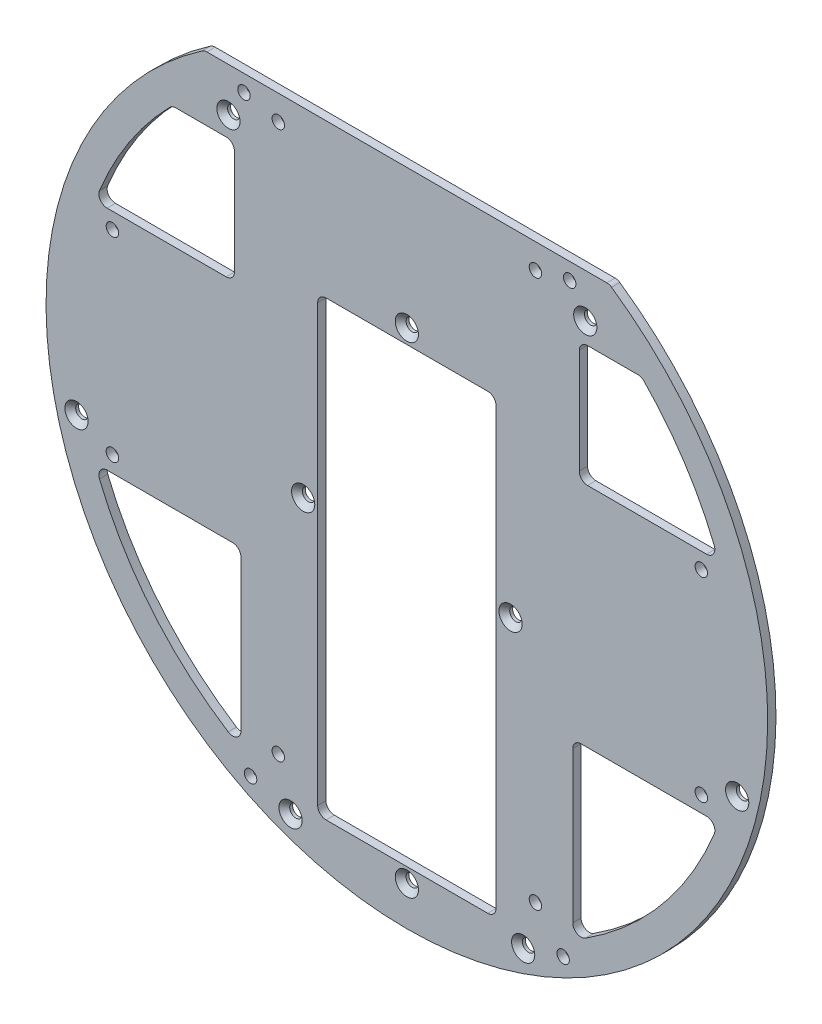
SolidWorks part; units mm, degrees
material "6061 Alloy"
ref_plane "Front Plane" through (0, 0, 0) normal (0, 0, 1) x (1, 0, 0)
ref_plane "Top Plane" through (0, 0, 0) normal (0, 1, 0) x (1, 0, 0)
ref_plane "Right Plane" through (0, 0, 0) normal (1, 0, 0) x (0, 0, -1)
ref_plane "Plane1" through (0, 0, 0) normal (0, 0, -1) x (-1, 0, 0)
sketch "Sketch1" plane through (0, 0, 0) normal (0, 0, -1) x (-1, 0, 0)
  line L0 (50, 72) -> (34.5, 72)
  line L1 (32.5, 70) -> (32.5, 50.75)
  line L2 (30.5, 48.75) -> (-30.5, 48.75)
  line L3 (-32.5, 50.75) -> (-32.5, 69.75)
  line L4 (-34.5, 71.75) -> (-50, 71.75)
  line L5 (-53.75, 68) -> (-53.75, 40.75)
  line L6 (-51.75, 38.75) -> (-39, 38.75)
  line L7 (-35, 34.75) -> (-35, -46)
  line L8 (-39, -50) -> (-45.095, -50)
  line L9 (45.095, -50) -> (39, -50)
  line L10 (35, -46) -> (35, 34.75)
  line L11 (39, 38.75) -> (51.75, 38.75)
  line L12 (53.75, 40.75) -> (53.75, 68.25)
  line L13 (0, 0) -> (0, -87) construction
  line L14 (0, 0) -> (49.3488, 65.4881) construction
  line L15 (0, 0) -> (-49.3488, 65.4881) construction
  line L16 (0, 0) -> (28.0457, -77.0548) construction
  line L17 (0, 0) -> (-28.0457, -77.0548) construction
  circle A9 centre (49.3488, 65.4881) radius 1.5
  circle A10 centre (-49.3488, 65.4881) radius 1.5
  circle A32 centre (28.0457, -77.0548) radius 1.5
  circle A33 centre (-28.0457, -77.0548) radius 1.5
  arc A34 (34.5, 72) -> (32.5, 70) centre (34.5, 70) ccw
  arc A35 (32.5, 50.75) -> (30.5, 48.75) centre (30.5, 50.75) cw
  arc A36 (-30.5, 48.75) -> (-32.5, 50.75) centre (-30.5, 50.75) cw
  arc A37 (-32.5, 69.75) -> (-34.5, 71.75) centre (-34.5, 69.75) ccw
  arc A38 (-50, 71.75) -> (-53.75, 68) centre (-50, 68) ccw
  arc A39 (-53.75, 40.75) -> (-51.75, 38.75) centre (-51.75, 40.75) ccw
  arc A40 (-39, 38.75) -> (-35, 34.75) centre (-39, 34.75) cw
  arc A41 (-35, -46) -> (-39, -50) centre (-39, -46) cw
  arc A42 (-45.095, -50) -> (-53.095, -66) centre (-45.095, -60) ccw
  arc A43 (-53.095, -66) -> (-39.0482, -77.7447) centre (-21.095, -42) ccw
  arc A44 (-39.0482, -77.7447) -> (39.0482, -77.7447) centre (0, 0) ccw
  arc A45 (39.0482, -77.7447) -> (53.095, -66) centre (21.095, -42) ccw
  arc A46 (53.095, -66) -> (45.095, -50) centre (45.095, -60) ccw
  arc A47 (39, -50) -> (35, -46) centre (39, -46) cw
  arc A48 (35, 34.75) -> (39, 38.75) centre (39, 34.75) cw
  arc A49 (51.75, 38.75) -> (53.75, 40.75) centre (51.75, 40.75) ccw
  arc A50 (53.75, 68.25) -> (50, 72) centre (50, 68.25) ccw
  dimension "D1" = 72
extrude "Boss-Extrude1" add sketch "Sketch1" against normal blind 2
sketch "Sketch2" plane through (0, 0, 2) normal (0, 0, 1) x (1, 0, 0)
  line L0 (0, 0) -> (-41.5, -71.8801) construction
  line L1 (0, 0) -> (41.5, -71.8801) construction
  line L2 (0, 0) -> (39.2598, 68) construction
  line L3 (0, 0) -> (-39.2598, 68) construction
  line L4 (-47.2117, 68) -> (64.0051, 68) construction
  dimension "D1" = 68
hole_wizard "M3 Clearance Hole1" positions "3DSketch1" profile "Sketch3" hole size "M3" standard "ANSI Metric"
sketch3d "3DSketch1"
  point P0 (-39.2598, 68, 2)
  point P3 (39.2598, 68, 2)
sketch "Sketch3" plane through (-39.2598, 68, 2) normal (1, 0, 0) x (0, -1, 0)
  line L0 (0, 0) -> (0, 2.9013)
  line L1 (0, 2.9013) -> (1.5, 2)
  line L2 (1.5, 2) -> (1.5, 0)
  line L5 (1.5, 0) -> (0, 0)
  line L10 (0, 2.9013) -> (-1.5, 2) construction
  line L11 (0, -6.35) -> (0, 107.95) construction
  dimension "Hole Dia." = 3
  dimension "Hole Depth" = 2
  dimension "Drill Angle" = 118
sketch "Sketch4" plane through (0, 0, 2) normal (0, 0, 1) x (1, 0, 0)
  line L1 (-35, 48.75) -> (35, 48.75)
  line L2 (-35, 48.75) -> (-35, -71.25)
  line L3 (-35, -71.25) -> (35, -71.25)
  line L4 (35, 48.75) -> (35, -71.25)
  circle A0 centre (30, 43.75) radius 1.75
  circle A1 centre (-30.9476, 44.2545) radius 1.75
  circle A2 centre (-28.7884, -65.1797) radius 1.75
  circle A3 centre (29.3815, -65.1797) radius 1.75
  circle A4 centre (30, -11.25) radius 1.75
  circle A5 centre (-30.9476, -11.25) radius 1.75
  dimension "D3" = 5
  dimension "D5" = 3.5
  dimension "D1" = 70
  dimension "D2" = 120
  dimension "D4" = 5
sketch "Sketch5" plane through (0, 0, 2) normal (0, 0, 1) x (1, 0, 0)
  line L0 (-48.8365, 72) -> (48.8365, 72)
  arc A0 (-48.8365, 72) -> (48.8365, 72) centre (0, 0) ccw
  circle A1 centre (-39.2598, 68) radius 1.6
  circle A3 centre (39.2598, 68) radius 1.6
  circle A5 centre (-28.0457, -77.0548) radius 1.6
  circle A7 centre (28.0457, -77.0548) radius 1.6
  point P4 (0, 72)
  dimension "D1" = 87
  dimension "D2" = 72
extrude "Boss-Extrude2" add sketch "Sketch5" against normal blind 2
sketch "Sketch6" plane through (0, 0, 2) normal (0, 0, 1) x (1, 0, 0)
  line L0 (49.203, 71.75) -> (50, 71.75) construction
  line L1 (-37.5, -71.75) -> (37.5, -71.75) construction
  line L2 (-37.5, -71.75) -> (-37.5, 71.75) construction
  line L3 (-37.5, 71.75) -> (37.5, 71.75) construction
  line L4 (37.5, -71.75) -> (37.5, 71.75) construction
  line L5 (-37.5, -71.75) -> (37.5, 71.75) construction
  line L6 (-37.5, 71.75) -> (37.5, -71.75) construction
  line L7 (-75.1754, -27.3616) -> (-40, -27.3616)
  line L8 (-76.6596, -27.5) -> (-41.6596, -27.5) construction
  line L10 (-76.6596, 27.5) -> (-41.6596, 27.5) construction
  line L14 (42.931, -27.5) -> (77.931, -27.5) construction
  line L16 (42.931, 27.5) -> (77.931, 27.5) construction
  line L20 (-40, -27.3616) -> (-40, -69.282)
  line L21 (41.5685, 27.3616) -> (75.1754, 27.3616)
  line L22 (41.5685, 56.5685) -> (41.5685, 27.3616)
  line L23 (56.5685, 56.5685) -> (41.5685, 56.5685)
  line L24 (40, -27.3616) -> (40, -69.282)
  line L25 (75.1754, -27.3616) -> (40, -27.3616)
  line L26 (-56.5685, 56.5685) -> (-41.5685, 56.5685)
  line L27 (-41.5685, 56.5685) -> (-41.5685, 27.3616)
  line L28 (-41.5685, 27.3616) -> (-75.1754, 27.3616)
  line L30 (0, 0) -> (-56.5685, 56.5685) construction
  line L31 (0, 0) -> (40, -69.282) construction
  line L32 (0, 0) -> (-75.1754, 27.3616) construction
  line L33 (0, 0) -> (75.1754, -27.3616) construction
  line L34 (0, 71.75) -> (0, -87) construction
  line L35 (0, 0) -> (75.1754, 27.3616) construction
  line L36 (0, 0) -> (56.5685, 56.5685) construction
  line L38 (0, 0) -> (-75.1754, -27.3616) construction
  line L39 (0, 0) -> (-40, -69.282) construction
  arc A0 (-75.1754, -27.3616) -> (-40, -69.282) centre (0, 0) ccw
  arc A1 (75.1754, 27.3616) -> (56.5685, 56.5685) centre (0, 0) ccw
  arc A2 (75.1754, -27.3616) -> (40, -69.282) centre (0, 0) cw
  arc A3 (-75.1754, 27.3616) -> (-56.5685, 56.5685) centre (0, 0) cw
  point P0 (0, 0)
  point P8 (-59.1596, 0)
  point P13 (60.431, 0)
  dimension "D1" = 45
  dimension "D7" = 80
  dimension "D2" = 70
  dimension "D3" = 30
  dimension "D4" = 70
  dimension "D5" = 15
  dimension "D6" = 80
extrude "Cut-Extrude1" cut sketch "Sketch6" against normal blind 2
sketch "Sketch7" plane through (0, 0, 2) normal (0, 0, 1) x (1, 0, 0)
  line L0 (35, 27.5) -> (35, 70)
  line L1 (-75, -27.5) -> (-35, -27.5)
  line L2 (-75, -27.5) -> (-75, 27.5)
  line L3 (-75, 27.5) -> (-35, 27.5)
  line L4 (75, -27.5) -> (75, 27.5)
  line L7 (-35, -70) -> (35, -70)
  line L8 (-35, -70) -> (-35, -27.5)
  line L9 (-35, 70) -> (35, 70)
  line L10 (35, -70) -> (35, -27.5)
  line L13 (35, 27.5) -> (75, 27.5)
  line L14 (35, -27.5) -> (75, -27.5)
  line L17 (-35, 27.5) -> (-35, 70)
  point P0 (0, 0)
  point P6 (0, 0)
  dimension "D1" = 40
  dimension "D2" = 70
  dimension "D3" = 40
  dimension "D4" = 42.5
  dimension "D5" = 55
  dimension "D6" = 42.5
sketch "Sketch8" plane through (0, 0, 2) normal (0, 0, 1) x (1, 0, 0)
  circle A0 centre (0, 0) radius 87
  circle A1 centre (0, 0) radius 97
  dimension "D1" = 10
extrude "Cut-Extrude2" cut sketch "Sketch8" against normal blind 10
sketch "Sketch10" plane through (0, 0, 2) normal (0, 0, 1) x (1, 0, 0)
  line L0 (-48.8365, 72) -> (48.8365, 72) construction
  line L1 (-21.5, -74) -> (21.5, -74)
  line L2 (-21.5, -74) -> (-21.5, 35)
  line L3 (-21.5, 35) -> (21.5, 35)
  line L4 (21.5, -74) -> (21.5, 35)
  line L5 (-21.5, -74) -> (21.5, 35) construction
  line L6 (-21.5, 35) -> (21.5, -74) construction
  point P0 (0, -19.5)
  dimension "D1" = 43
  dimension "D2" = 109
  dimension "D3" = 37
extrude "Cut-Extrude3" cut sketch "Sketch10" against normal blind 10
sketch "Sketch11" plane through (0, 0, 2) normal (0, 0, 1) x (1, 0, 0)
  line L0 (0, 0) -> (-43.0182, 61.4364) construction
  line L1 (0, 0) -> (37.6812, -73.9535) construction
  line L2 (0, 72) -> (0, 0) construction
  line L4 (21.5, 35) -> (-21.5, 35) construction
  line L5 (-21.5, -74) -> (21.5, -74) construction
  line L6 (21.5, -74) -> (21.5, 35) construction
  line L7 (-21.5, 35) -> (-21.5, -74) construction
  line L8 (-79.6477, -19.5) -> (79.6477, -19.5) construction
  line L9 (0, 0) -> (-75, 0) construction
  line L10 (-75, 27.5) -> (-71, 27.5)
  line L11 (-75, 27.5) -> (-75, 23.5)
  line L12 (-75, 23.5) -> (-71, 23.5)
  line L13 (-71, 27.5) -> (-71, 23.5)
  line L14 (-35, 70) -> (-31, 70)
  line L15 (-35, 70) -> (-35, 66)
  line L16 (-35, 66) -> (-31, 66)
  line L17 (-31, 70) -> (-31, 66)
  line L18 (-75, -27.5) -> (-75, 27.5) construction
  line L19 (-31, -70) -> (-31, -66)
  line L20 (-35, -66) -> (-31, -66)
  line L21 (-35, -70) -> (-35, -66)
  line L22 (-35, -70) -> (-31, -70)
  line L23 (-71, -27.5) -> (-71, -23.5)
  line L24 (-75, -23.5) -> (-71, -23.5)
  line L25 (-75, -27.5) -> (-75, -23.5)
  line L26 (-75, -27.5) -> (-71, -27.5)
  line L27 (35, -70) -> (31, -70)
  line L28 (35, -70) -> (35, -66)
  line L29 (35, -66) -> (31, -66)
  line L30 (31, -70) -> (31, -66)
  line L31 (75, -27.5) -> (71, -27.5)
  line L32 (75, -27.5) -> (75, -23.5)
  line L33 (75, -23.5) -> (71, -23.5)
  line L34 (71, -27.5) -> (71, -23.5)
  line L35 (71, 27.5) -> (71, 23.5)
  line L36 (75, 23.5) -> (71, 23.5)
  line L37 (75, 27.5) -> (75, 23.5)
  line L38 (75, 27.5) -> (71, 27.5)
  line L39 (31, 70) -> (31, 66)
  line L40 (35, 66) -> (31, 66)
  line L41 (35, 70) -> (35, 66)
  line L42 (35, 70) -> (31, 70)
  line L43 (0, 0) -> (-37.6812, -73.9535) construction
  line L44 (0, 0) -> (43.0182, 61.4364) construction
  line L45 (0, 0) -> (-28.0457, -77.0548) construction
  line L46 (-25, -9.5) -> (25, -9.5) construction
  line L47 (-48.8365, 72) -> (48.8365, 72) construction
  arc A0 (-48.8365, 72) -> (48.8365, 72) centre (0, 0) ccw construction
  point P0 (25, -9.5)
  point P1 (-25, -9.5)
  point P2 (0, -77.5)
  point P3 (0, 38.5)
  point P4 (-43.0182, 61.4364)
  point P23 (0, -19.5)
  point P66 (21.5, -19.5)
  dimension "D2" = 35
  dimension "D4" = 75
  dimension "D5" = 3.5
  dimension "D6" = 3.5
  dimension "D7" = 3.5
  dimension "D8" = 3.5
  dimension "D9" = 82
  dimension "D10" = 4
  dimension "D11" = 83
  dimension "D12" = 27
  dimension "D13" = 10
hole_wizard "CSK for M3 SFHCS1" positions "3DSketch2" profile "Sketch12" countersink size "M3" standard "ANSI Metric"
sketch3d "3DSketch2"
  line L0 (-28.0457, -77.0548, 2) -> (-28.0457, -77.0548, 0) construction
  line L2 (28.0457, -77.0548, 2) -> (28.0457, -77.0548, 0) construction
  point P0 (0, 38.5, 2)
  point P3 (-25, -9.5, 2)
  point P9 (0, -77.5, 2)
  point P12 (-79.6477, -19.5, 2)
  point P15 (79.6477, -19.5, 2)
  point P18 (-43.0182, 61.4364, 2)
  point P25 (-28.0457, -77.0548, 2)
  point P33 (43.0182, 61.4364, 2)
  point P39 (25, -9.5, 2)
  point P45 (28.0457, -77.0548, 2)
sketch "Sketch12" plane through (0, 38.5, 2) normal (1, 0, 0) x (0, -1, 0)
  line L0 (0, 0) -> (0, 10.4013)
  line L1 (0, 10.4013) -> (1.5, 9.5)
  line L2 (1.5, 9.5) -> (1.5, 1.3)
  line L3 (1.5, 1.3) -> (2.8, 0)
  line L5 (2.8, 0) -> (0, 0)
  line L6 (-1.5, 1.3) -> (-2.8, 0) construction
  line L10 (0, 10.4013) -> (-1.5, 9.5) construction
  line L11 (0, -6.35) -> (0, 107.95) construction
  dimension "Hole Dia." = 3
  dimension "Hole Depth" = 9.5
  dimension "Near C'Sink Dia." = 5.6
  dimension "Near C'Sink Angle" = 90
  dimension "Drill Angle" = 118
hole_wizard "Ø3.0 (3) Diameter Hole1" positions "3DSketch3" profile "Sketch13" hole size "Ø3.0" standard "ANSI Metric"
sketch3d "3DSketch3"
  point P0 (-71, 23.5, 2)
  point P3 (-71, -23.5, 2)
  point P6 (-31, -66, 2)
  point P9 (-37.6812, -73.9535, 2)
  point P27 (-31, 66, 2)
  point P32 (31, 66, 2)
  point P35 (71, 23.5, 2)
  point P52 (31, -66, 2)
  point P55 (71, -23.5, 2)
  point P60 (37.6812, -73.9535, 2)
sketch "Sketch13" plane through (-71, 23.5, 2) normal (1, 0, 0) x (0, -1, 0)
  line L0 (0, 0) -> (0, 3.9013)
  line L1 (0, 3.9013) -> (1.5, 3)
  line L2 (1.5, 3) -> (1.5, 0)
  line L5 (1.5, 0) -> (0, 0)
  line L10 (0, 3.9013) -> (-1.5, 3) construction
  line L11 (0, -6.35) -> (0, 107.95) construction
  dimension "Hole Dia." = 3
  dimension "Hole Depth" = 3
  dimension "Drill Angle" = 118
fillet "Fillet1" radius 2 20 edges at (-75.1754, -27.3616, 1) (-40, -69.282, 1) (40, -69.282, 1) (75.1754, -27.3616, 1) (-40, -27.3616, 1) (41.5685, 56.5685, 1) (56.5685, 56.5685, 1) (40, -27.3616, 1) (41.5685, 27.3616, 1) (75.1754, 27.3616, 1) (-41.5685, 27.3616, 1) (-41.5685, 56.5685, 1) (-75.1754, 27.3616, 1) (-56.5685, 56.5685, 1) (21.5, -74, 1) (-21.5, -74, 1) (-21.5, 35, 1) (21.5, 35, 1) (48.8365, 72, 1) (-48.8365, 72, 1)
